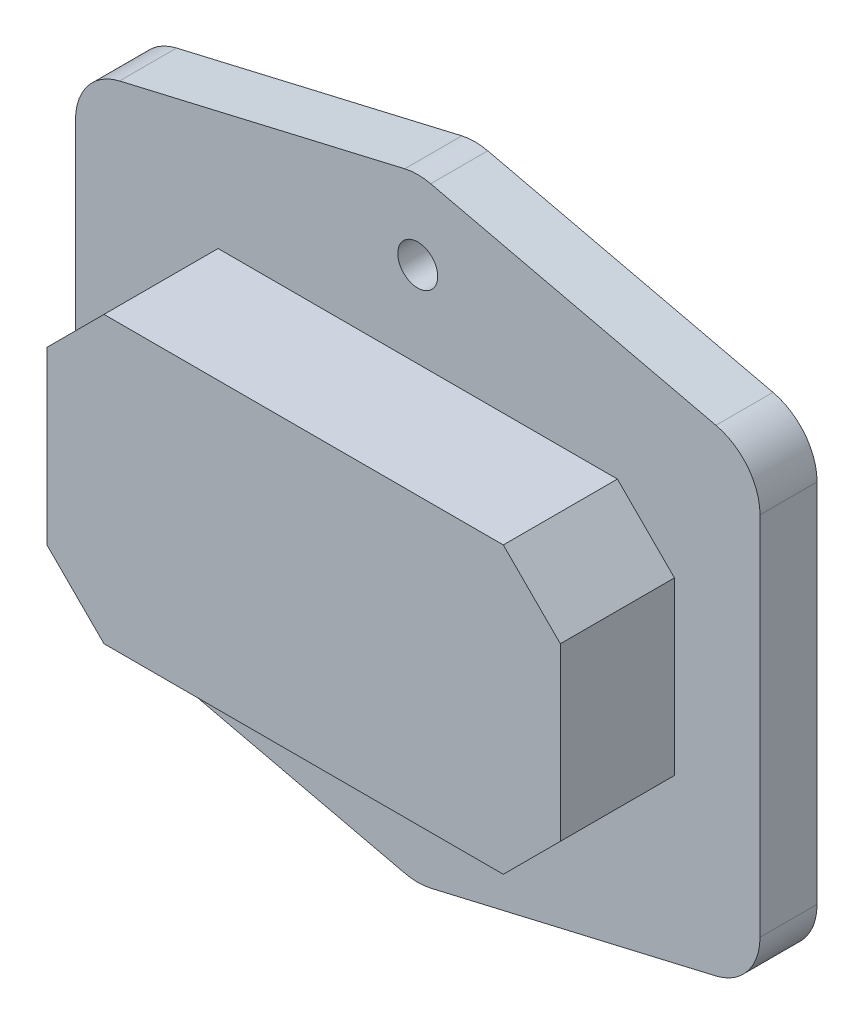
SolidWorks part; units mm, degrees
ref_plane "Front Plane" through (0, 0, 0) normal (0, 0, 1) x (1, 0, 0)
ref_plane "Top Plane" through (0, 0, 0) normal (0, 1, 0) x (1, 0, 0)
ref_plane "Right Plane" through (0, 0, 0) normal (1, 0, 0) x (0, 0, -1)
sketch "Sketch1" plane through (0, 0, 0) normal (0, 0, 1) x (1, 0, 0)
  line L1 (-22.5, -12.5) -> (22.5, -12.5)
  line L2 (-22.5, -12.5) -> (-22.5, 12.5)
  line L3 (-22.5, 12.5) -> (22.5, 12.5)
  line L4 (22.5, -12.5) -> (22.5, 12.5)
  line L5 (-22.5, -12.5) -> (22.5, 12.5) construction
  line L6 (-22.5, 12.5) -> (22.5, -12.5) construction
  point P0 (0, 0)
  dimension "D1" = 45
  dimension "D2" = 25
extrude "Boss-Extrude1" add sketch "Sketch1" along normal blind 10
sketch "Sketch2" plane through (0, 0, 0) normal (0, 0, -1) x (-1, 0, 0)
  line L0 (0, 0) -> (0, 20) construction
  line L2 (-30, 20) -> (-30, -20)
  line L4 (30, 20) -> (30, -20)
  line L5 (-30, 20) -> (30, -20) construction
  line L6 (-30, -20) -> (30, 20) construction
  line L7 (0, 0) -> (0, -20) construction
  line L8 (0, 20) -> (0, 27) construction
  line L9 (0, -20) -> (0, -27) construction
  line L10 (-30, 20) -> (0, 27)
  line L11 (0, 27) -> (30, 20)
  line L12 (30, -20) -> (0, -27)
  line L13 (0, -27) -> (-30, -20)
  circle A1 centre (0, 20) radius 1.75
  circle A2 centre (0, -20) radius 1.75
  point P0 (0, 0)
  dimension "D5" = 3.5
  dimension "D6" = 3.5
  dimension "D7" = 7
  dimension "D8" = 7
  dimension "D1" = 40
  dimension "D2" = 60
  dimension "D3" = 20
  dimension "D4" = 20
  dimension "D9" = 30
extrude "Boss-Extrude2" add sketch "Sketch2" along normal blind 5
fillet "Fillet1" radius 5 6 edges at (0, 27, -2.5) (-30, 20, -2.5) (-30, -20, -2.5) (0, -27, -2.5) (30, -20, -2.5) (30, 20, -2.5)
sketch "Sketch3" plane through (0, 0, -5) normal (0, 0, -1) x (-1, 0, 0)
  line L0 (0, 20) -> (0, -20) construction
  line L1 (5, 10) -> (5, -10)
  line L2 (5, -10) -> (15, -10)
  line L3 (15, -10) -> (20, -5)
  line L4 (20, -5) -> (20, 5)
  line L5 (20, 5) -> (15, 10)
  line L6 (15, 10) -> (5, 10)
  dimension "D1" = 20
  dimension "D2" = 15
  dimension "D3" = 10
  dimension "D4" = 10
  dimension "D5" = 10
  dimension "D6" = 5
  dimension "D7" = 5
  dimension "D8" = 10
extrude "Cut-Extrude1" cut sketch "Sketch3" against normal blind 10
ref_plane "Plane1" through (5, 0, 0) normal (1, 0, 0) x (0, 0, -1)
sketch "Sketch4" plane through (5, 0, 0) normal (1, 0, 0) x (0, 0, -1)
  line L0 (5, 16.0324) -> (5, -16.0324) construction
  line L2 (5, 10) -> (6, 10)
  line L3 (5, 10) -> (5, -10)
  line L4 (5, -10) -> (6, -10)
  line L5 (6, 10) -> (6, -10)
  dimension "D1" = 1
  dimension "D2" = 20
  dimension "D3" = 10
extrude "Boss-Extrude3" add sketch "Sketch4" along normal blind 15
ref_plane "Plane2" through (7, 0, 0) normal (1, 0, 0) x (0, 0, -1)
sketch "Sketch5" plane through (7, 0, 0) normal (1, 0, 0) x (0, 0, -1)
  line L0 (6, 8) -> (7.5, 8)
  line L1 (6, -10) -> (6, 10) construction
  line L2 (7.5, 8) -> (7.5, 0)
  line L3 (7.5, 0) -> (11.5, -6.9282)
  line L4 (6, -8) -> (6, 8)
  line L6 (6, 10) -> (5, 10) construction
  arc A0 (11.5, -6.9282) -> (6, -8) centre (7.1912, 0.5348) cw
  point P11 (5.5, 10)
  dimension "D1" = 2
  dimension "D2" = 16
  dimension "D3" = 8
  dimension "D4" = 8
  dimension "D5" = 150
  dimension "D6" = 1.5
extrude "Boss-Extrude4" add sketch "Sketch5" along normal blind 11
chamfer "Chamfer1" distance 5 angle 45 4 edges at (22.5, -12.5, 5) (22.5, 12.5, 5) (-22.5, -12.5, 5) (-22.5, 12.5, 5)
